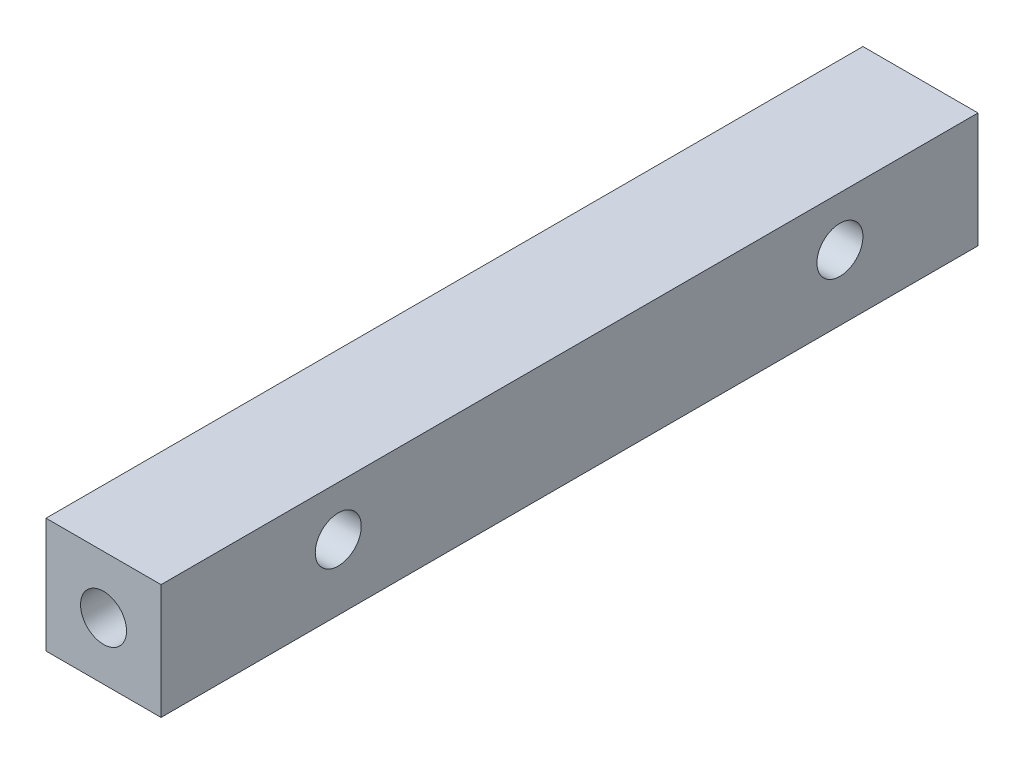
SolidWorks part; units mm, degrees
ref_plane "Plan de face" through (0, 0, 0) normal (0, 0, 1) x (1, 0, 0)
ref_plane "Plan de dessus" through (0, 0, 0) normal (0, 1, 0) x (1, 0, 0)
ref_plane "Plan de droite" through (0, 0, 0) normal (1, 0, 0) x (0, 0, -1)
sketch "Esquisse1" plane through (0, 0, 0) normal (0, 0, 1) x (1, 0, 0)
  line L1 (0, 0) -> (10, 0)
  line L2 (0, 0) -> (0, 10)
  line L3 (0, 10) -> (10, 10)
  line L4 (10, 0) -> (10, 10)
  dimension "D1" = 10
  dimension "D2" = 10
extrude "Boss.-Extru.1" add sketch "Esquisse1" along normal blind 71
sketch "Esquisse2" plane through (0, 0, 0) normal (-1, 0, 0) x (0, 0, 1)
  line L0 (63.827, 5.7) -> (-7.5908, 5.7) construction
  line L1 (71, 0) -> (0, 0) construction
  line L2 (0, 10) -> (0, 0) construction
  circle A0 centre (12, 5.7) radius 2
  circle A1 centre (55.6, 5.7) radius 2
  dimension "D4" = 4
  dimension "D5" = 4
  dimension "D1" = 5.7
  dimension "D2" = 12
  dimension "D3" = 43.6
extrude "Enlèv. mat.-Extru.1" cut sketch "Esquisse2" against normal through all
sketch "Esquisse3" plane through (0, 0, 0) normal (0, 0, -1) x (-1, 0, 0)
  line L0 (0, 10) -> (0, 0) construction
  line L2 (0, 0) -> (-10, 0) construction
  circle A0 centre (-5, 5) radius 2
  dimension "D1" = 4
  dimension "D2" = 5
  dimension "D3" = 5
extrude "Enlèv. mat.-Extru.2" cut sketch "Esquisse3" against normal blind 6
sketch "Esquisse4" plane through (0, 0, 71) normal (0, 0, 1) x (1, 0, 0)
  line L0 (0, 10) -> (0, 0) construction
  line L1 (0, 0) -> (10, 0) construction
  circle A0 centre (5, 5) radius 2
  dimension "D1" = 4
  dimension "D2" = 5
  dimension "D3" = 5
extrude "Enlèv. mat.-Extru.3" cut sketch "Esquisse4" against normal blind 6
